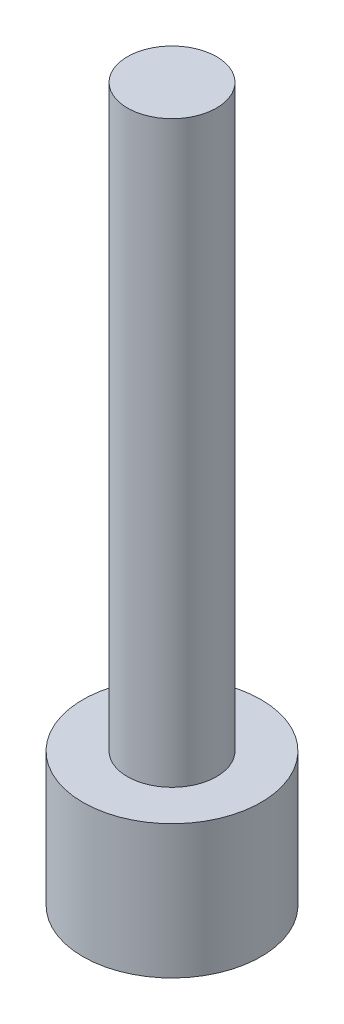
SolidWorks part; units mm, degrees
ref_plane "Front Plane" through (0, 0, 0) normal (0, 0, 1) x (1, 0, 0)
ref_plane "Top Plane" through (0, 0, 0) normal (0, 1, 0) x (1, 0, 0)
ref_plane "Right Plane" through (0, 0, 0) normal (1, 0, 0) x (0, 0, -1)
sketch "Sketch1" plane through (0, 0, 0) normal (0, 1, 0) x (1, 0, 0)
  circle A0 centre (0, 0) radius 1
  dimension "D1" = 2
extrude "Boss-Extrude1" add sketch "Sketch1" along normal blind 13
sketch "Sketch2" plane through (0, 0, 0) normal (0, -1, 0) x (1, 0, 0)
  circle A0 centre (0, 0) radius 2
extrude "Boss-Extrude2" add sketch "Sketch2" along normal blind 3
